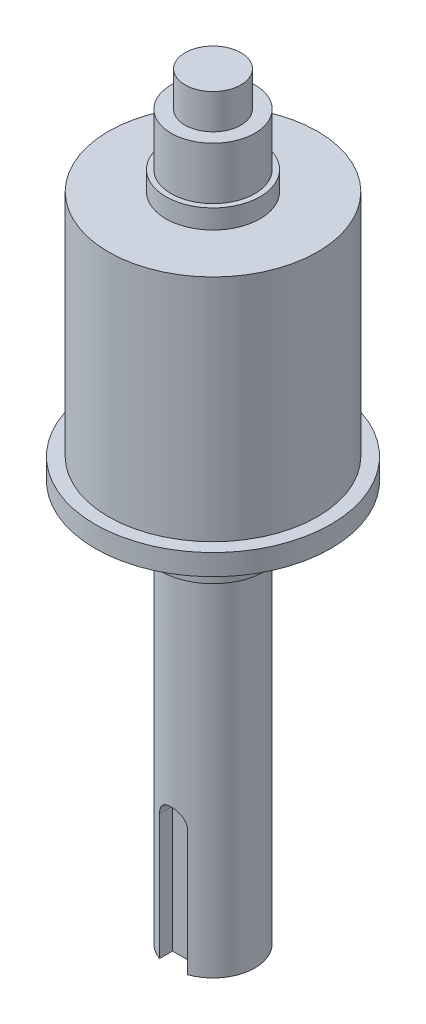
SolidWorks part; units mm, degrees
material "AISI 1035 Steel (SS)"
ref_plane "Front Plane" through (0, 0, 0) normal (0, 0, 1) x (1, 0, 0)
ref_plane "Top Plane" through (0, 0, 0) normal (0, 1, 0) x (1, 0, 0)
ref_plane "Right Plane" through (0, 0, 0) normal (1, 0, 0) x (0, 0, -1)
sketch "Sketch2" plane through (0, 0, 0) normal (0, 0, 1) x (1, 0, 0)
  line L0 (0, 40.0334) -> (0, -27.2464) construction
  line L11 (0, 0) -> (-4, 0)
  line L12 (-4, 0) -> (-4, -5)
  line L13 (-4, -5) -> (-6, -5)
  line L14 (-6, -5) -> (-6, -12.5)
  line L15 (-6, -12.5) -> (-6.75, -12.5)
  line L16 (-6.75, -12.5) -> (-6.75, -15.25)
  line L17 (-6.75, -15.25) -> (-14.9815, -15.25)
  line L18 (-14.9815, -15.25) -> (-14.9815, -48.11)
  line L26 (0, -108.61) -> (0, 0)
  line L28 (-16.8815, -51.11) -> (-16.8815, -48.11)
  line L29 (-16.8815, -48.11) -> (-14.9815, -48.11)
  line L30 (-16.8815, -51.11) -> (-8.25, -51.11)
  line L31 (-8.25, -51.11) -> (-8.25, -53.61)
  line L32 (-14.9815, -48.11) -> (-14.9815, -51.11) construction
  line L33 (-8.25, -53.61) -> (-7.5, -53.61)
  line L34 (-7.5, -53.61) -> (-7.5, -58.61)
  line L35 (-7.5, -58.61) -> (-6, -58.61)
  line L36 (-6, -58.61) -> (-6, -108.61)
  line L37 (-6, -108.61) -> (0, -108.61)
  dimension "D1" = 4
  dimension "D2" = 5
  dimension "D3" = 6
  dimension "D4" = 7.5
  dimension "D5" = 6.75
  dimension "D6" = 2.75
  dimension "D7" = 14.9815
  dimension "D8" = 32.86
  dimension "D10" = 3
  dimension "D11" = 8.25
  dimension "D12" = 2.5
  dimension "D13" = 7.5
  dimension "D14" = 5
  dimension "D15" = 6
  dimension "D16" = 50
  dimension "D9" = 1.9
revolve "Revolve1" add sketch "Sketch2" angle 360 about L0
sketch "Sketch3" plane through (0, -108.61, 0) normal (0, -1, 0) x (1, 0, 0)
  line L4 (-2, 5.6569) -> (-2, 7.8) construction
  line L5 (-2, 7.8) -> (2, 7.8) construction
  line L6 (2, 7.8) -> (2, 5.6569) construction
  line L7 (0, -6) -> (12.9978, -6) construction
  line L8 (-2, 5.6569) -> (-2, 3.8)
  line L9 (-2, 3.8) -> (2, 3.8)
  line L10 (2, 3.8) -> (2, 5.6569)
  circle A1 centre (0, 0) radius 6
  arc A2 (2, 5.6569) -> (-2, 5.6569) centre (0, 0) ccw
  point P2 (0, 7.8)
  dimension "D2" = 4
  dimension "D3" = 13.8
  dimension "D4" = 4
extrude "Cut-Extrude1" cut sketch "Sketch3" against normal blind 15
sketch "Sketch4" plane through (0, 0, 3.8) normal (0, 0, 1) x (1, 0, 0)
  line L0 (-2, -93.61) -> (-2, -90.61)
  line L1 (2, -90.61) -> (2, -93.61)
  line L2 (-4.5886, -88.61) -> (3.957, -88.61) construction
  line L3 (-2, -108.61) -> (2, -108.61) construction
  line L4 (-2, -93.61) -> (-2, -108.61)
  line L5 (-2, -108.61) -> (2, -108.61)
  line L6 (2, -108.61) -> (2, -93.61)
  arc A0 (-2, -90.61) -> (2, -90.61) centre (0, -90.61) cw
  dimension "D1" = 20
extrude "Cut-Extrude2" cut sketch "Sketch4" along normal through all
equation "\"Stator_OD\"= 60'No Tolerance given"
equation "\"A\"=35.81 'taken off spec sheet for 06808 (A)"
equation "\"Rotor_ID\"= 30'No Tolerance Given"
equation "\"back_bearing_Thickness\"= 5'-0.12"
equation "\"back_bearing_OD\"= 24'-0.009 https://www.mcmaster.com/5972K155/"
equation "\"Stator_Gap\"= 0.0375'+- 0.0125 (From 1.3.3.1 Kollmorgen manual)"
equation "\"Back_mount_hole\"= 1.75'To be tapped to M2 (USE LOCKTITE)"
equation "\"facePlate_Mount_Hole\"= 2.75'To be tapped to M3"
equation "\"final_shaftD\"= 12'To fit in harmonic"
equation "\"back_bearing_ID\"= 15'"
equation "\"rotor_shaftD\"= \"Rotor_ID\" - (\"rotor-shaft_gap\")*2'"
equation "\"back_bearing_IDOD\"= 16.5'measured off CAD, actually 16.75, but rounded down to nicer number"
equation "\"final_shaftL\"= 50'random length. Idk"
equation "\"D1@Sketch2\"=4"
equation "\"D3@Sketch2\"=\"front_bearing_ID\"/2"
equation "\"D4@Sketch2\" = \"front_bearing_Thickness\" + 2.5"
equation "\"D5@Sketch2\"=\"front_bearing_IDOD\" / 2"
equation "\"D8@Sketch2\"=\"rotor_height\""
equation "\"front_bearing_ID\"= 12'https://www.mcmaster.com/5972K154/"
equation "\"front_bearing_OD\"= 21'-0.009"
equation "\"front_bearing_IDOD\"= 13.5'Measured off CAD. Actually 13.75, but rounded down"
equation "\"front_bearing_Thickness\"= 5'-0.12"
equation "\"rotor_thickness\"= 2.4'measured off CAD"
equation "\"rotor_height\"= 32.86'+-0.075 taken off spec sheet for 06826 (C)"
equation "\"D11@Sketch2\"=\"back_bearing_IDOD\"/2"
equation "\"D13@Sketch2\"=\"back_bearing_ID\"/2"
equation "\"D14@Sketch2\"=\"back_bearing_Thickness\""
equation "\"D15@Sketch2\"=\"final_shaftD\"/2"
equation "\"D16@Sketch2\"=\"final_shaftL\""
equation "\"D9@Sketch2\"=\"rotor_thickness\"-0.5"
equation "\"rotor-shaft_gap\" = 0.0185 '+-0.0065 (from manual)"
equation "\"D7@Sketch2\"=\"Rotor_ID\"/2-\"rotor-shaft_gap\""
equation "\"B\"= 26.3'+-0.35 taken off spec sheet for 06826"
equation "\"key_L\"= 20'-0.2 https://www.mcmaster.com/2977N19/"
equation "\"key_H\"= 4'-0.03"
equation "\"key_W\"= 4'-0.03"
equation "\"harmon_keyH\"= 13.8'+0.1"
equation "\"harmon_coupleL\"= 21.5' taken from CAD"
equation "\"D2@Sketch3\"=\"key_W\""
equation "\"D3@Sketch3\"=\"harmon_keyH\""
equation "\"D4@Sketch3\"=\"key_H\""
equation "\"D1@Cut-Extrude1\"=\"key_L\"-5"
equation "\"D1@Sketch4\"=\"key_L\""
